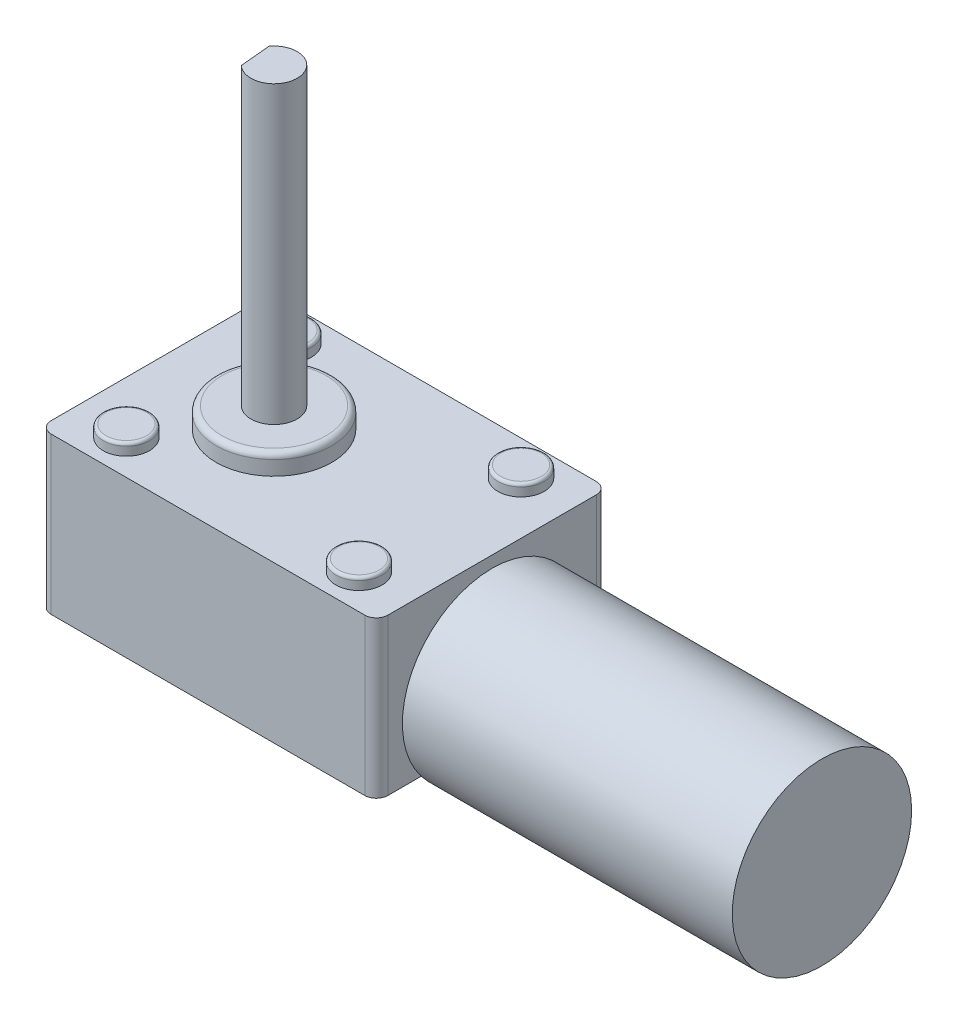
SolidWorks part; units mm, degrees
material "PPS"
ref_plane "Front Plane" through (0, 0, 0) normal (0, 0, 1) x (1, 0, 0)
ref_plane "Top Plane" through (0, 0, 0) normal (0, 1, 0) x (1, 0, 0)
ref_plane "Right Plane" through (0, 0, 0) normal (1, 0, 0) x (0, 0, -1)
sketch "Sketch1" plane through (0, 0, 0) normal (0, 1, 0) x (1, 0, 0)
  line L1 (-66.0502, 26.1223) -> (-7.8502, 26.1223)
  line L2 (-66.0502, 26.1223) -> (-66.0502, -13.8777)
  line L3 (-66.0502, -13.8777) -> (-7.8502, -13.8777)
  line L4 (-7.8502, 26.1223) -> (-7.8502, -13.8777)
  dimension "D1" = 58.2
  dimension "D2" = 40
extrude "Boss-Extrude1" add sketch "Sketch1" along normal blind 27
fillet "Fillet1" radius 2 4 edges at (-7.8502, 13.5, -26.1223) (-66.0502, 13.5, -26.1223) (-66.0502, 13.5, 13.8777) (-7.8502, 13.5, 13.8777)
sketch "Sketch2" plane through (-7.8502, 0, 0) normal (1, 0, 0) x (0, 0, -1)
  line L0 (-11.8777, 27) -> (24.1223, 27) construction
  circle A0 centre (6.1223, 9.5) radius 15.5
  point P4 (6.1223, 27)
  point P5 (6.1223, 25)
  dimension "D1" = 31
  dimension "D2" = 0
  dimension "D3" = 2
extrude "Boss-Extrude2" add sketch "Sketch2" along normal blind 57
sketch "Sketch3" plane through (0, 27, 0) normal (0, 1, 0) x (1, 0, 0)
  line L0 (-66.0502, 24.1223) -> (-66.0502, -11.8777) construction
  line L1 (-7.8502, -11.8777) -> (-7.8502, 24.1223) construction
  line L2 (-64.0502, -13.8777) -> (-9.8502, -13.8777) construction
  line L3 (-9.8502, 26.1223) -> (-64.0502, 26.1223) construction
  circle A0 centre (-16.8502, -7.8777) radius 4
  circle A1 centre (-16.8502, 20.1223) radius 4
  circle A2 centre (-57.0502, -7.8777) radius 4
  circle A3 centre (-57.0502, 20.1223) radius 4
  dimension "D9" = 8
  dimension "D10" = 8
  dimension "D11" = 8
  dimension "D12" = 8
  dimension "D1" = 9
  dimension "D2" = 9
  dimension "D3" = 9
  dimension "D4" = 9
  dimension "D5" = 6
  dimension "D6" = 6
  dimension "D7" = 6
  dimension "D8" = 6
extrude "Boss-Extrude3" add sketch "Sketch3" along normal blind 2
sketch "Sketch4" plane through (0, 27, 0) normal (0, 1, 0) x (1, 0, 0)
  line L0 (-66.0502, 6.1223) -> (-19.9157, 6.1223) construction
  line L1 (-66.0502, 24.1223) -> (-66.0502, -11.8777) construction
  circle A0 centre (-45.53, 6.1223) radius 10
  dimension "D1" = 20
extrude "Boss-Extrude4" add sketch "Sketch4" along normal blind 3.5
ref_plane "Plane1" through (0, 13.5, 0) normal (0, 1, 0) x (1, 0, 0)
mirror "Mirror1" about plane through (0, 13.5, 0) normal (0, 1, 0) of "Boss-Extrude3", "Boss-Extrude4"
fillet "Fillet2" radius 0.5 4 edges at (-57.0502, 29, 11.8777) (-57.0502, 29, -16.1223) (-16.8502, 29, -16.1223) (-16.8502, 29, 11.8777)
fillet "Fillet3" radius 1 1 edges at (-45.53, 30.5, 3.8777)
mirror "Mirror6" about plane through (0, 13.5, 0) normal (0, 1, 0) of "Boss-Extrude3", "Boss-Extrude4"
fillet "Fillet4" radius 0.5 4 edges at (-57.0502, -2, -16.1223) (-57.0502, -2, 11.8777) (-16.8502, -2, 11.8777) (-16.8502, -2, -16.1223)
fillet "Fillet5" radius 1 1 edges at (-45.53, -3.5, 3.8777)
sketch "Sketch5" plane through (0, 30.5, 0) normal (0, 1, 0) x (1, 0, 0)
  line L0 (-48.2704, 3.2086) -> (-48.7634, 8.4771)
  line L1 (-48.5169, 5.8428) -> (-38.4886, 6.7812) construction
  arc A0 (-48.2704, 3.2086) -> (-48.7634, 8.4771) centre (-45.53, 6.1223) ccw
  point P7 (-41.5474, 6.495)
  dimension "D1" = 8
  dimension "D2" = 7
extrude "Boss-Extrude5" add sketch "Sketch5" along normal blind 51
